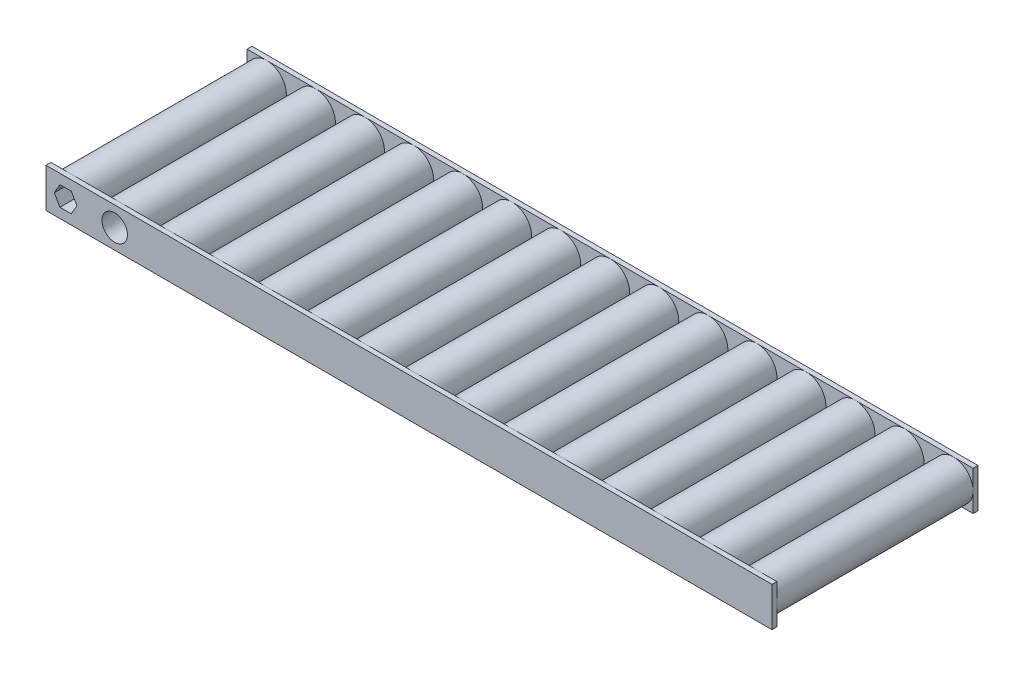
SolidWorks part; units mm, degrees
ref_plane "Front Plane" through (0, 0, 0) normal (0, 0, 1) x (1, 0, 0)
ref_plane "Top Plane" through (0, 0, 0) normal (0, 1, 0) x (1, 0, 0)
ref_plane "Right Plane" through (0, 0, 0) normal (1, 0, 0) x (0, 0, -1)
sketch "Sketch1" plane through (0, 0, 0) normal (0, 0, 1) x (1, 0, 0)
  circle A0 centre (0, 0) radius 12.7
  dimension "D1" = 25.4
extrude "Boss-Extrude1" add sketch "Sketch1" along normal blind 127 contours A0
pattern_linear "LPattern1" count 15 spacing 31.75 along (1, 0, 0) of "Boss-Extrude1"
sketch "Sketch2" plane through (0, 0, 127) normal (0, 0, 1) x (1, 0, 0)
  line L0 (-12.7, 12.7) -> (-12.7, -12.7)
  line L1 (-12.7, -12.7) -> (457.2, -12.7)
  line L2 (457.2, -12.7) -> (457.2, 12.7)
  line L3 (457.2, 12.7) -> (-12.7, 12.7)
  point P2 (0, 0)
  dimension "D1" = 469.9
  dimension "D2" = 25.4
extrude "Boss-Extrude2" add sketch "Sketch2" along normal blind 3.175
ref_plane "Plane1" through (0, 0, 63.5) normal (0, 0, 1) x (1, 0, 0)
mirror "Mirror1" about plane through (0, 0, 63.5) normal (0, 0, 1) of "Boss-Extrude2"
sketch "Sketch3" plane through (0, 0, 130.175) normal (0, 0, 1) x (1, 0, 0)
  line L1 (7.3323, 0) -> (3.6662, 6.35)
  line L2 (31.75, -12.7) -> (63.5, -12.7)
  line L3 (63.5, 12.7) -> (31.75, 12.7)
  line L6 (3.6662, 6.35) -> (-3.6662, 6.35)
  line L7 (-3.6662, 6.35) -> (-7.3323, 0)
  line L8 (-7.3323, 0) -> (-3.6662, -6.35)
  line L9 (-3.6662, -6.35) -> (3.6662, -6.35)
  line L10 (3.6662, -6.35) -> (7.3323, 0)
  arc A0 (0, 12.7) -> (-12.7, 0) centre (0, 0) ccw construction
  arc A1 (0, -12.7) -> (0, 12.7) centre (0, 0) ccw construction
  arc A2 (31.75, -12.7) -> (31.75, 12.7) centre (31.75, 0) ccw
  arc A3 (63.5, 12.7) -> (63.5, -12.7) centre (63.5, 0) ccw
  arc A4 (31.75, -12.7) -> (31.75, 12.7) centre (31.75, 0) ccw construction
  arc A6 (31.75, 12.7) -> (31.75, -12.7) centre (31.75, 0) ccw construction
  arc A7 (0, 12.7) -> (-12.7, 0) centre (0, 0) ccw construction
  arc A8 (0, -12.7) -> (0, 12.7) centre (0, 0) ccw construction
  arc A9 (31.75, 12.7) -> (31.75, -12.7) centre (31.75, 0) ccw construction
  circle A10 centre (31.75, 0) radius 8.255
  circle A11 centre (0, 0) radius 6.35 construction
  dimension "D2" = 16.51
  dimension "D3" = 12.7
  dimension "D1" = 0
extrude "Cut-Extrude1" cut sketch "Sketch3" against normal through all
